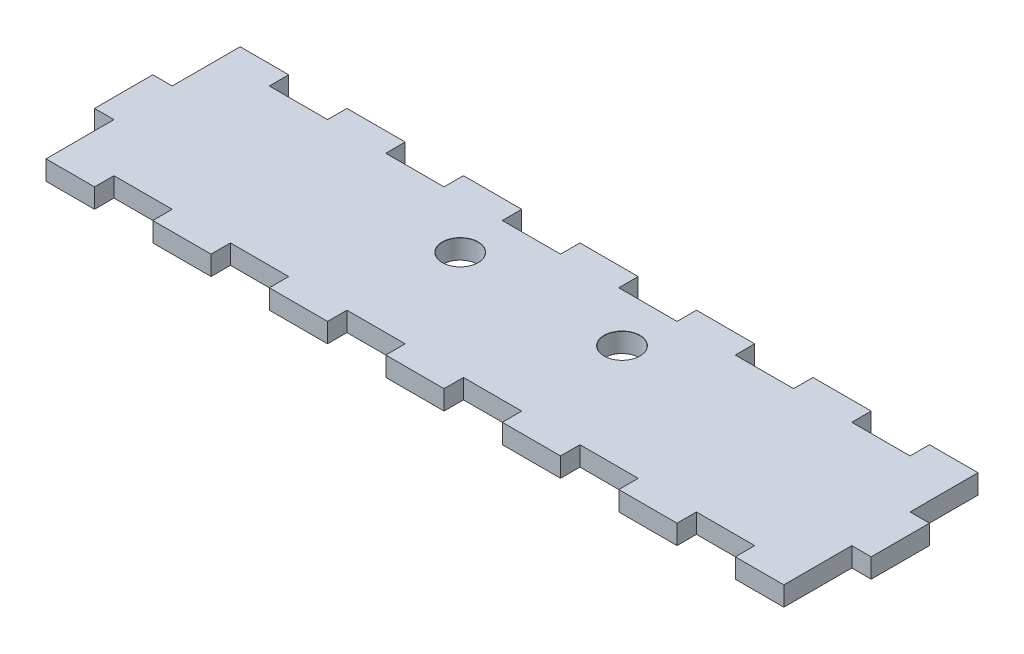
SolidWorks part; units mm, degrees
ref_plane "Front Plane" through (0, 0, 0) normal (0, 0, 1) x (1, 0, 0)
ref_plane "Top Plane" through (0, 0, 0) normal (0, 1, 0) x (1, 0, 0)
ref_plane "Right Plane" through (0, 0, 0) normal (1, 0, 0) x (0, 0, -1)
sketch "Sketch1" plane through (0, 0, 0) normal (0, 1, 0) x (1, 0, 0)
  line L0 (57, 15) -> (49.5, 15)
  line L1 (49.5, 15) -> (49.5, 12)
  line L2 (49.5, 12) -> (40.5, 12)
  line L3 (40.5, 12) -> (40.5, 15)
  line L4 (40.5, 15) -> (31.5, 15)
  line L5 (31.5, 15) -> (31.5, 12)
  line L6 (31.5, 12) -> (22.5, 12)
  line L7 (22.5, 12) -> (22.5, 15)
  line L8 (22.5, 15) -> (13.5, 15)
  line L9 (13.5, 15) -> (13.5, 12)
  line L10 (13.5, 12) -> (4.5, 12)
  line L11 (4.5, 12) -> (4.5, 15)
  line L12 (4.5, 15) -> (-4.5, 15)
  line L13 (-4.5, 15) -> (-4.5, 12)
  line L14 (-4.5, 12) -> (-13.5, 12)
  line L15 (-13.5, 12) -> (-13.5, 15)
  line L16 (-13.5, 15) -> (-22.5, 15)
  line L17 (-22.5, 15) -> (-22.5, 12)
  line L18 (-22.5, 12) -> (-31.5, 12)
  line L19 (-31.5, 12) -> (-31.5, 15)
  line L20 (-31.5, 15) -> (-40.5, 15)
  line L21 (-40.5, 15) -> (-40.5, 12)
  line L22 (-40.5, 12) -> (-49.5, 12)
  line L23 (-49.5, 12) -> (-49.5, 15)
  line L24 (-49.5, 15) -> (-57, 15)
  line L25 (-57, 15) -> (-57, 12)
  line L26 (-57, 12) -> (-57, 4.5)
  line L27 (-57, 4.5) -> (-60, 4.5)
  line L28 (-60, 4.5) -> (-60, -4.5)
  line L29 (-60, -4.5) -> (-57, -4.5)
  line L30 (-57, -4.5) -> (-57, -12)
  line L31 (-57, -12) -> (-57, -15)
  line L32 (-57, -15) -> (-49.5, -15)
  line L33 (-49.5, -15) -> (-49.5, -12)
  line L34 (-49.5, -12) -> (-40.5, -12)
  line L35 (-40.5, -12) -> (-40.5, -15)
  line L36 (-40.5, -15) -> (-31.5, -15)
  line L37 (-31.5, -15) -> (-31.5, -12)
  line L38 (-31.5, -12) -> (-22.5, -12)
  line L39 (-22.5, -12) -> (-22.5, -15)
  line L40 (-22.5, -15) -> (-13.5, -15)
  line L41 (-13.5, -15) -> (-13.5, -12)
  line L42 (-13.5, -12) -> (-4.5, -12)
  line L43 (-4.5, -12) -> (-4.5, -15)
  line L44 (-4.5, -15) -> (4.5, -15)
  line L45 (4.5, -15) -> (4.5, -12)
  line L46 (4.5, -12) -> (13.5, -12)
  line L47 (13.5, -12) -> (13.5, -15)
  line L48 (13.5, -15) -> (22.5, -15)
  line L49 (22.5, -15) -> (22.5, -12)
  line L50 (22.5, -12) -> (31.5, -12)
  line L51 (31.5, -12) -> (31.5, -15)
  line L52 (31.5, -15) -> (40.5, -15)
  line L53 (40.5, -15) -> (40.5, -12)
  line L54 (40.5, -12) -> (49.5, -12)
  line L55 (49.5, -12) -> (49.5, -15)
  line L56 (49.5, -15) -> (57, -15)
  line L57 (57, -15) -> (57, -12)
  line L58 (57, -12) -> (57, -4.5)
  line L59 (57, -4.5) -> (60, -4.5)
  line L60 (60, -4.5) -> (60, 4.5)
  line L61 (60, 4.5) -> (57, 4.5)
  line L62 (57, 4.5) -> (57, 12)
  line L63 (57, 12) -> (57, 15)
  line L64 (-60, 4.5) -> (-60, 15) construction
  line L65 (-60, 15) -> (-57, 15) construction
  line L66 (60, -4.5) -> (60, -15) construction
  line L67 (60, -15) -> (57, -15) construction
  line L68 (-60, 15) -> (60, -15) construction
  point P64 (0, 0)
extrude "Boss-Extrude1" add sketch "Sketch1" along normal mid plane 3
sketch "Sketch2" plane through (0, 1.5, 0) normal (0, 1, 0) x (1, 0, 0)
  text T0 "Front/Back"
extrude "Cut-Extrude1" [suppressed] cut sketch "Sketch2" against normal blind 1
sketch "Sketch3" plane through (0, 1.5, 0) normal (0, 1, 0) x (1, 0, 0)
  line L0 (0, 29.7636) -> (0, -33.9988) construction
  line L1 (-12.5, 4.5) -> (12.5, 4.5) construction
  line L3 (-31.5, 15) -> (-40.5, 15) construction
  point P3 (-12.5, 4.5)
  point P4 (12.5, 4.5)
  point P9 (12.5, 4.5)
  point P10 (-12.5, 4.5)
  point P11 (0, 4.5)
  dimension "D1" = 25
  dimension "D3" = 10.5
hole_wizard "M5 Clearance Hole1" positions "Sketch3" profile "Sketch4" hole size "M5" standard "ISO" end condition through all
sketch "Sketch4" plane through (-12.5, 1.5, -4.5) normal (1, 0, 0) x (0, 0, 1)
  line L0 (0, 0) -> (0, 3)
  line L1 (0, 3) -> (2.75, 3)
  line L2 (2.75, 3) -> (2.75, 0.025)
  line L3 (2.75, 0.025) -> (2.775, 0)
  line L5 (2.775, 0) -> (0, 0)
  line L6 (-2.75, 0.025) -> (-2.775, 0) construction
  line L11 (0, -6.35) -> (0, 107.95) construction
  dimension "Thru Hole Dia." = 5.5
  dimension "Thru Hole Depth" = 3
  dimension "Near C'Sink Dia." = 5.55
  dimension "Near C'Sink Angle" = 90
